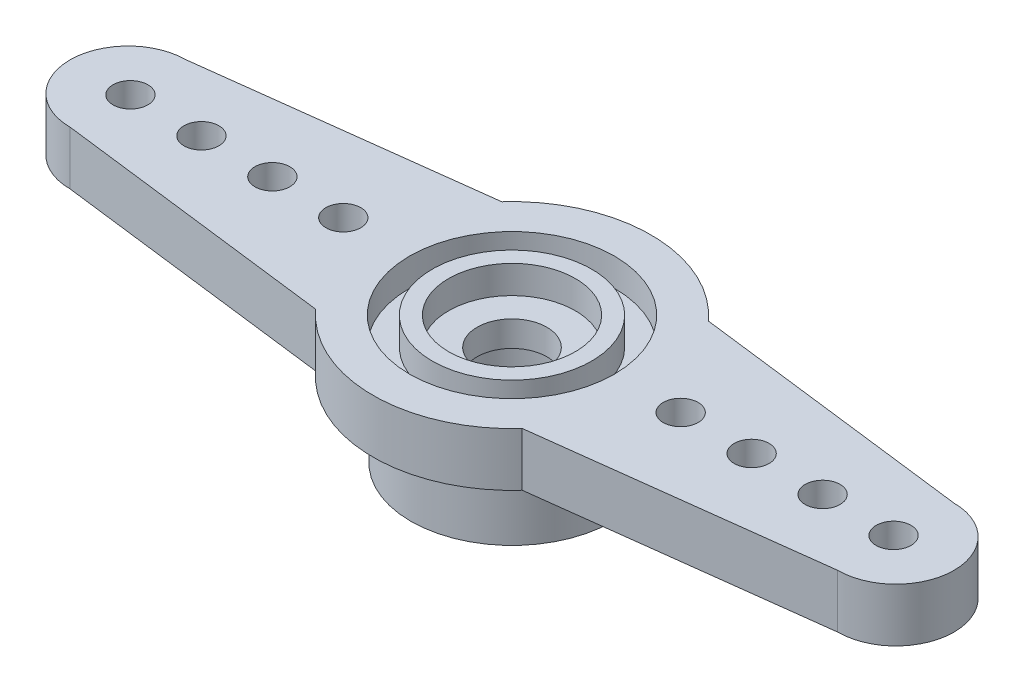
SolidWorks part; units mm, degrees
ref_plane "Спереди" through (0, 0, 0) normal (0, 0, 1) x (1, 0, 0)
ref_plane "Сверху" through (0, 0, 0) normal (0, 1, 0) x (1, 0, 0)
ref_plane "Справа" through (0, 0, 0) normal (1, 0, 0) x (0, 0, -1)
sketch "Эскиз1" plane through (0, 0, 0) normal (0, 1, 0) x (1, 0, 0)
  line L0 (0, 0) -> (19, 0) construction
  line L2 (4.4385, 4) -> (4.4385, -4) construction
  line L3 (4.4385, 4) -> (16.5, 2.5)
  line L4 (4.4385, -4) -> (16.5, -2.5)
  line L5 (-4.4385, 4) -> (-16.5, 2.5)
  line L6 (-16.5, -2.5) -> (-4.4385, -4)
  line L7 (6.5, 0) -> (11.05, 0) construction
  line L8 (8, 0) -> (-1.5, 0) construction
  line L9 (-8, 0) -> (1.5, 0) construction
  arc A0 (-4.4385, -4) -> (4.4385, -4) centre (0, 0) ccw
  circle A1 centre (0, 0) radius 1.5
  arc A2 (16.5, -2.5) -> (16.5, 2.5) centre (16.5, 0) ccw
  arc A3 (-16.5, 2.5) -> (-16.5, -2.5) centre (-16.5, 0) ccw
  arc A4 (4.4385, 4) -> (-4.4385, 4) centre (0, 0) ccw
  circle A5 centre (10.3, 0) radius 0.75
  circle A6 centre (13.35, 0) radius 0.75
  circle A7 centre (16.4, 0) radius 0.75
  circle A8 centre (-10.3, 0) radius 0.75
  circle A9 centre (-13.35, 0) radius 0.75
  circle A10 centre (-16.4, 0) radius 0.75
  circle A11 centre (7.25, 0) radius 0.75
  circle A12 centre (-7.25, 0) radius 0.75
  dimension "D1" = 2.5
  dimension "D3" = 3.05
  dimension "D4" = 3.05
  dimension "D5" = 3.05
  dimension "D6" = 3.05
  dimension "D7" = 3.05
  dimension "D8" = 3.05
extrude "Бобышка-Вытянуть1" add sketch "Эскиз1" along normal blind 2.3
sketch "Эскиз2" plane through (0, 0, 0) normal (0, -1, 0) x (1, 0, 0)
  circle A0 centre (0, 0) radius 4.35
  circle A1 centre (0, 0) radius 2.45
  dimension "D1" = 1.9
extrude "Бобышка-Вытянуть2" add sketch "Эскиз2" along normal blind 3.2
sketch "Эскиз3" plane through (0, 2.3, 0) normal (0, 1, 0) x (1, 0, 0)
  circle A0 centre (0, 0) radius 3.425
  circle A1 centre (0, 0) radius 4.4
  circle A2 centre (0, 0) radius 2.725
  circle M13 centre (0, 0) radius 1.5
  dimension "D1" = 0.7
extrude "Вырез-Вытянуть1" cut sketch "Эскиз3" against normal blind 1.2 contours A1 A0 | A2 M13
sketch "Эскиз4" plane through (0, 2.3, 0) normal (0, 1, 0) x (1, 0, 0)
  line L0 (19, 0) -> (-19, 0) construction
  arc A0 (16.5, -2.5) -> (16.5, 2.5) centre (16.5, 0) ccw construction
  arc A1 (-16.5, 2.5) -> (-16.5, -2.5) centre (-16.5, 0) ccw construction
sketch "草图1" plane through (0, 2.3, 0) normal (0, 1, 0) x (1, 0, 0)
  line L0 (-16.5298, 0) -> (16.4, 0)
